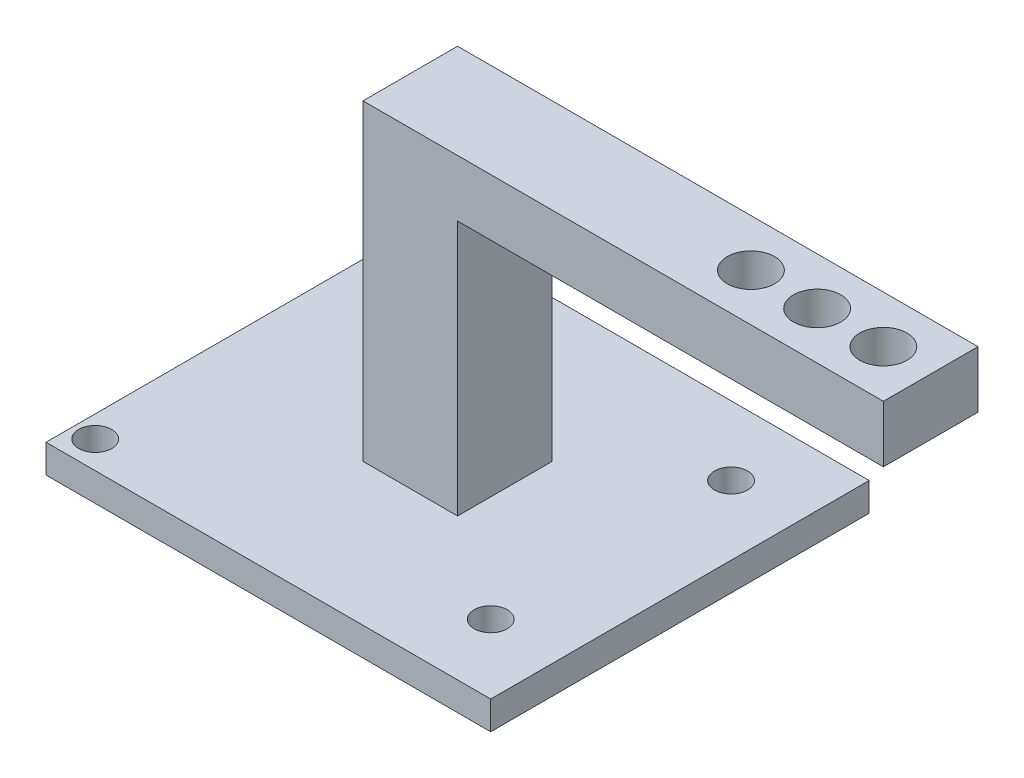
SolidWorks part; units mm, degrees
ref_plane "Front Plane" through (0, 0, 0) normal (0, 0, 1) x (1, 0, 0)
ref_plane "Top Plane" through (0, 0, 0) normal (0, 1, 0) x (1, 0, 0)
ref_plane "Right Plane" through (0, 0, 0) normal (1, 0, 0) x (0, 0, -1)
sketch "Sketch1" plane through (0, 0, 0) normal (0, 1, 0) x (1, 0, 0)
  line L0 (0, 0) -> (47, 0)
  line L1 (47, 0) -> (47, 40)
  line L2 (47, 40) -> (0, 40)
  line L3 (0, 40) -> (0, 0)
  line L4 (0, 40) -> (-2, 40)
  line L5 (-2, 40) -> (-2, 0)
  line L6 (-2, 0) -> (0, 0)
  circle A0 centre (39.7, 7.3) radius 1.75
  circle A1 centre (39.7, 32.7) radius 1.75
  circle A2 centre (2.3, 37.1) radius 1.75
  circle A3 centre (2.3, 2.9) radius 1.75
  dimension "D3" = 7.3
  dimension "D5" = 3.5
  dimension "D6" = 3.5
  dimension "D9" = 3.5
  dimension "D13" = 3.5
  dimension "D1" = 47
  dimension "D2" = 40
  dimension "D4" = 7.3
  dimension "D7" = 7.3
  dimension "D8" = 7.3
  dimension "D10" = 2.9
  dimension "D11" = 37.4
  dimension "D12" = 2
  dimension "D14" = 2.9
extrude "Boss-Extrude1" add sketch "Sketch1" along normal blind 3 contours L2 L3 L0 L1 A3 A2 A1 A0
sketch "Sketch2" plane through (0, 3, 0) normal (0, 1, 0) x (1, 0, 0)
  line L0 (47, 40) -> (0, 40) construction
  line L1 (18.5, 25) -> (28.5, 25)
  line L2 (18.5, 25) -> (18.5, 15)
  line L3 (18.5, 15) -> (28.5, 15)
  line L4 (28.5, 25) -> (28.5, 15)
  line L6 (0, 40) -> (0, 0) construction
  point P6 (18.5, 20)
  dimension "D1" = 10
  dimension "D2" = 10
  dimension "D3" = 15
  dimension "D4" = 18.5
extrude "Boss-Extrude3" add sketch "Sketch2" along normal blind 27
sketch "Sketch3" plane through (0, 30, 0) normal (0, 1, 0) x (1, 0, 0)
  line L0 (18.5, 25) -> (28.5, 25)
  line L1 (18.5, 25) -> (28.5, 25)
  line L2 (18.5, 25) -> (18.5, 15)
  line L3 (18.5, 15) -> (28.5, 15)
  line L4 (28.5, 25) -> (28.5, 15)
  line L5 (73.5, 25) -> (73.5, 15)
  line L6 (73.5, 15) -> (18.5, 15)
  line L7 (18.5, 25) -> (73.5, 25)
  line M6 (18.5, 25) -> (18.5, 15)
  line M7 (18.5, 15) -> (28.5, 15)
  line M8 (28.5, 15) -> (28.5, 25)
  line M9 (28.5, 25) -> (18.5, 25)
  dimension "D1" = 55
extrude "Boss-Extrude4" add sketch "Sketch3" along normal blind 6 contours L7 L6 L5 M8 | M9 M6 M7 M8
sketch "Sketch4" plane through (0, 36, 0) normal (0, 1, 0) x (1, 0, 0)
  line L1 (18.5, 25) -> (73.5, 25)
  line L2 (18.5, 25) -> (18.5, 15)
  line L3 (18.5, 15) -> (73.5, 15)
  line L4 (73.5, 25) -> (73.5, 15)
extrude "Cut-Extrude1" cut sketch "Sketch4" against normal blind 6
sketch "Sketch5" plane through (0, 30, 0) normal (0, 1, 0) x (1, 0, 0)
  line L0 (18.5, 25) -> (73.5, 25)
  line L1 (18.5, 15) -> (73.5, 15)
  line L2 (73.5, 15) -> (73.5, 25)
  line L3 (18.5, 25) -> (18.5, 15)
  dimension "D1" = 55
extrude "Boss-Extrude5" add sketch "Sketch5" along normal blind 6
sketch "Sketch6" plane through (0, 36, 0) normal (0, 1, 0) x (1, 0, 0)
  line L0 (18.5, 15) -> (73.5, 15) construction
  line L1 (73.5, 15) -> (73.5, 25) construction
  circle A0 centre (68.5, 20) radius 2.5
  circle A1 centre (61.5, 20) radius 2.5
  circle A2 centre (54.5, 20) radius 2.5
  dimension "D1" = 5
  dimension "D2" = 5
  dimension "D3" = 5
  dimension "D4" = 5
  dimension "D5" = 5
  dimension "D6" = 5
  dimension "D7" = 5
  dimension "D8" = 7
  dimension "D9" = 7
extrude "Cut-Extrude2" cut sketch "Sketch6" against normal through all
